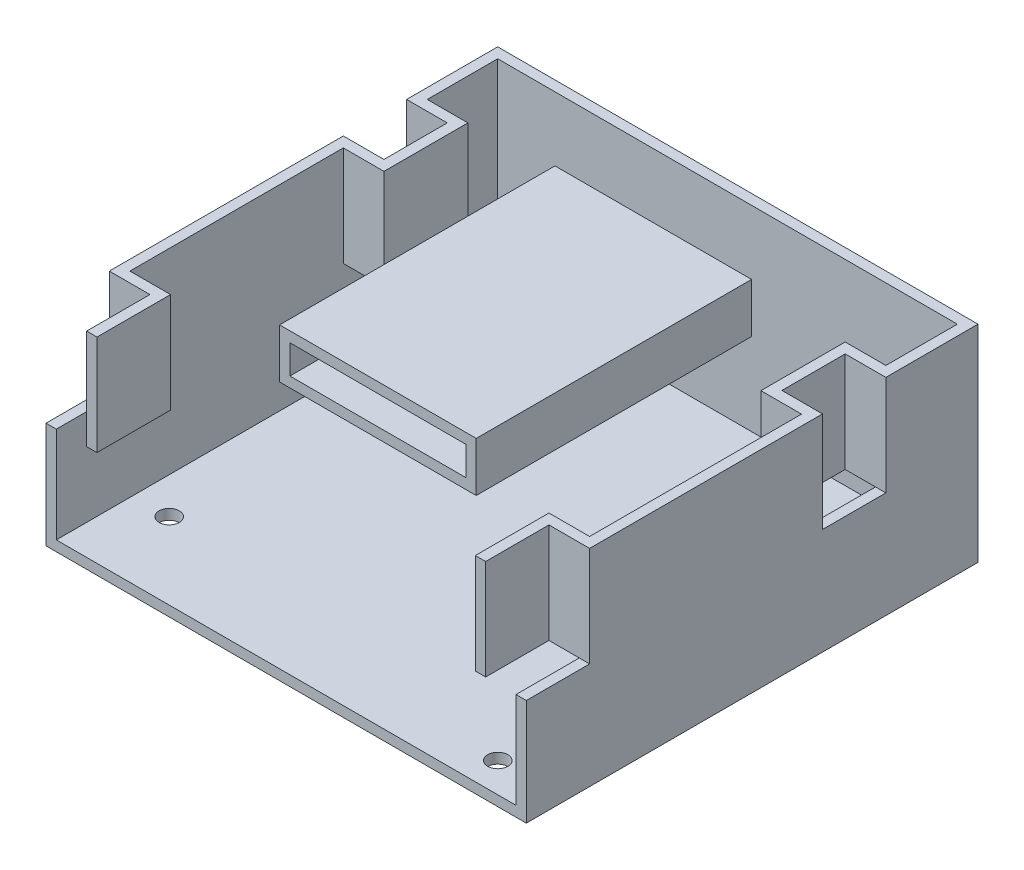
SolidWorks part; units mm, degrees
ref_plane "Front Plane" through (0, 0, 0) normal (0, 0, 1) x (1, 0, 0)
ref_plane "Top Plane" through (0, 0, 0) normal (0, 1, 0) x (1, 0, 0)
ref_plane "Right Plane" through (0, 0, 0) normal (1, 0, 0) x (0, 0, -1)
sketch "Sketch1" plane through (0, 0, 0) normal (0, 1, 0) x (1, 0, 0)
  line L1 (0, 0) -> (89.12, 0)
  line L2 (0, 0) -> (0, 85.57)
  line L3 (0, 85.57) -> (89.12, 85.57)
  line L4 (89.12, 0) -> (89.12, 85.57)
  dimension "D1" = 89.12
  dimension "D2" = 85.57
extrude "Boss-Extrude1" add sketch "Sketch1" along normal blind 2
sketch "Sketch3" plane through (0, 0, 0) normal (0, 0, 1) x (1, 0, 0)
  line L1 (0, 0) -> (-2, 0)
  line L2 (0, 0) -> (0, 30)
  line L3 (0, 30) -> (-2, 30)
  line L4 (-2, 0) -> (-2, 30)
  dimension "D1" = 2
  dimension "D2" = 30
extrude "Boss-Extrude2" add sketch "Sketch3" against normal blind 85.57
sketch "Sketch4" plane through (0, 0, 0) normal (0, 0, 1) x (1, 0, 0)
  line L1 (89.12, 0) -> (91.12, 0)
  line L2 (89.12, 0) -> (89.12, 30)
  line L3 (89.12, 30) -> (91.12, 30)
  line L4 (91.12, 0) -> (91.12, 30)
  dimension "D1" = 30
  dimension "D2" = 2
extrude "Boss-Extrude3" add sketch "Sketch4" against normal blind 85.57
sketch "Sketch5" plane through (0, 0, 0) normal (0, 1, 0) x (1, 0, 0)
  line L1 (-2, 85.57) -> (91.12, 85.57)
  line L2 (-2, 85.57) -> (-2, 87.57)
  line L3 (-2, 87.57) -> (91.12, 87.57)
  line L4 (91.12, 85.57) -> (91.12, 87.57)
  dimension "D1" = 2
extrude "Boss-Extrude4" add sketch "Sketch5" along normal blind 30
sketch "Sketch6" plane through (0, 0, 0) normal (0, 1, 0) x (1, 0, 0)
  line L0 (89.12, 0) -> (89.12, 5.755) construction
  line L1 (89.12, 0) -> (89.12, 85.57) construction
  line L2 (89.12, 5.755) -> (79.835, 5.755) construction
  line L3 (79.835, 5.755) -> (79.835, 0) construction
  line L4 (0, 0) -> (89.12, 0) construction
  circle A0 centre (79.835, 5.755) radius 1.96
  dimension "D3" = 3.92
extrude "Cut-Extrude2" cut sketch "Sketch6" along normal blind 30
sketch "Sketch7" plane through (0, 2, 0) normal (0, 1, 0) x (1, 0, 0)
  line L0 (89.12, 85.57) -> (82.285, 85.57) construction
  line L1 (0, 85.57) -> (89.12, 85.57) construction
  line L2 (82.285, 85.57) -> (82.285, 76.225) construction
  line L3 (82.285, 76.225) -> (89.12, 76.225) construction
  line L4 (89.12, 0) -> (89.12, 85.57) construction
  circle A0 centre (82.285, 76.225) radius 1.96
  dimension "D3" = 3.92
  dimension "D1" = 6.835
extrude "Cut-Extrude3" cut sketch "Sketch7" against normal blind 30
sketch "Sketch8" plane through (0, 0, 0) normal (0, 1, 0) x (1, 0, 0)
  line L0 (0, 85.57) -> (6.985, 85.57) construction
  line L1 (0, 85.57) -> (89.12, 85.57) construction
  line L2 (6.985, 85.57) -> (6.985, 78.28) construction
  line L3 (6.985, 78.28) -> (0, 78.28) construction
  line L4 (0, 85.57) -> (0, 0) construction
  circle A0 centre (6.985, 78.28) radius 1.96
  dimension "D3" = 3.92
  dimension "D1" = 7.29
extrude "Cut-Extrude4" cut sketch "Sketch8" along normal blind 30
sketch "Sketch9" plane through (0, 2, 0) normal (0, 1, 0) x (1, 0, 0)
  line L0 (0, 0) -> (0, 14.85) construction
  line L1 (0, 85.57) -> (0, 0) construction
  line L2 (0, 14.85) -> (7.035, 14.85) construction
  line L3 (7.035, 14.85) -> (7.035, 0) construction
  line L4 (0, 0) -> (89.12, 0) construction
  circle A0 centre (7.035, 14.85) radius 1.96
  dimension "D3" = 3.92
  dimension "D1" = 14.85
extrude "Cut-Extrude5" cut sketch "Sketch9" against normal blind 30
sketch "Sketch10" plane through (89.12, 0, 0) normal (-1, 0, 0) x (0, 0, 1)
  line L0 (0, 2) -> (0, 16.1) construction
  line L1 (0, 30) -> (0, 2) construction
  line L2 (0, 16.1) -> (-32.6241, 16.1) construction
  line L3 (-32.6241, 16.1) -> (-32.6241, 2) construction
  line L4 (0, 2) -> (-85.57, 2) construction
  line L5 (-32.6241, 16.1) -> (-32.6241, 30) construction
  line L6 (-85.57, 30) -> (0, 30) construction
  dimension "D1" = 14.1
sketch "Sketch11" plane through (0, 30, 0) normal (0, 1, 0) x (1, 0, 0)
  line L1 (89.12, 0) -> (83.24, 0)
  line L2 (89.12, 0) -> (89.12, 12.27)
  line L3 (89.12, 12.27) -> (83.24, 12.27)
  line L4 (83.24, 0) -> (83.24, 12.27)
  line L5 (83.24, 0) -> (81.24, 0)
  line L6 (83.24, 0) -> (83.24, 12.27)
  line L7 (83.24, 12.27) -> (81.24, 12.27)
  line L8 (81.24, 0) -> (81.24, 12.27)
  line L9 (81.24, 12.27) -> (89.12, 12.27)
  line L10 (81.24, 12.27) -> (81.24, 14.27)
  line L11 (81.24, 14.27) -> (89.12, 14.27)
  line L12 (89.12, 12.27) -> (89.12, 14.27)
  line M8 (89.12, 85.57) -> (89.12, 0)
  dimension "D1" = 5.88
  dimension "D2" = 12.27
  dimension "D3" = 2
  dimension "D4" = 2
extrude "Boss-Extrude5" add sketch "Sketch11" against normal blind 9.4 contours L11 L10 L7 L3 M8 | L8 L5 L4 L7
sketch "Sketch12" plane through (0, 30, 0) normal (0, 1, 0) x (1, 0, 0)
  line L1 (89.12, 12.27) -> (91.12, 12.27)
  line L2 (89.12, 12.27) -> (89.12, 0)
  line L3 (89.12, 0) -> (91.12, 0)
  line L4 (91.12, 12.27) -> (91.12, 0)
extrude "Cut-Extrude6" cut sketch "Sketch12" against normal blind 9.4
sketch "Sketch13" plane through (0, 30, 0) normal (0, 1, 0) x (1, 0, 0)
  line L0 (89.12, 85.57) -> (89.12, 57.43) construction
  line L1 (89.12, 85.57) -> (89.12, 14.27) construction
  line L3 (89.12, 57.43) -> (83.24, 57.43)
  line L4 (89.12, 57.43) -> (89.12, 69.7)
  line L5 (89.12, 69.7) -> (83.24, 69.7)
  line L6 (83.24, 57.43) -> (83.24, 69.7)
  line L7 (83.24, 69.7) -> (81.24, 69.7)
  line L8 (83.24, 69.7) -> (83.24, 57.43)
  line L9 (83.24, 57.43) -> (81.24, 57.43)
  line L10 (81.24, 69.7) -> (81.24, 57.43)
  line L11 (81.24, 57.43) -> (89.12, 57.43)
  line L12 (81.24, 57.43) -> (81.24, 55.3598)
  line L13 (81.24, 55.3598) -> (89.12, 55.3598)
  line L14 (89.12, 57.43) -> (89.12, 55.3598)
  line L15 (81.24, 69.7) -> (89.12, 69.7)
  line L16 (81.24, 69.7) -> (81.24, 71.7)
  line L17 (81.24, 71.7) -> (89.12, 71.7)
  line L18 (89.12, 69.7) -> (89.12, 71.7)
  line M25 (89.12, 85.57) -> (89.12, 14.27)
  dimension "D1" = 28.14
  dimension "D2" = 12.27
  dimension "D3" = 5.88
  dimension "D4" = 2
  dimension "D5" = 2.0702
  dimension "D6" = 2
extrude "Boss-Extrude6" add sketch "Sketch13" against normal blind 9.4 contours L17 L16 L7 L5 M25 | L7 L10 L9 L6 | L12 L13 L3 L9 M25
sketch "Sketch14" plane through (0, 30, 0) normal (0, 1, 0) x (1, 0, 0)
  line L0 (91.12, 87.57) -> (91.12, 12.27) construction
  line L1 (89.12, 69.7) -> (91.12, 69.7)
  line L2 (89.12, 69.7) -> (89.12, 57.43)
  line L3 (89.12, 57.43) -> (91.12, 57.43)
  line L4 (91.12, 69.7) -> (91.12, 57.43)
extrude "Cut-Extrude7" cut sketch "Sketch14" against normal blind 9.4
sketch "Sketch15" plane through (0, 30, 0) normal (0, 1, 0) x (1, 0, 0)
  line L0 (0, 85.57) -> (0, 57.64) construction
  line L1 (0, 85.57) -> (0, 0) construction
  line L3 (0, 57.64) -> (5.88, 57.64)
  line L4 (0, 57.64) -> (0, 69.91)
  line L5 (0, 69.91) -> (5.88, 69.91)
  line L6 (5.88, 57.64) -> (5.88, 69.91)
  line L7 (5.88, 69.91) -> (7.88, 69.91)
  line L8 (5.88, 69.91) -> (5.88, 57.64)
  line L9 (5.88, 57.64) -> (7.88, 57.64)
  line L10 (7.88, 69.91) -> (7.88, 57.64)
  line L11 (0, 57.64) -> (7.88, 57.64)
  line L12 (0, 57.64) -> (0, 55.64)
  line L13 (0, 55.64) -> (7.88, 55.64)
  line L14 (7.88, 57.64) -> (7.88, 55.64)
  line L15 (0, 69.91) -> (7.88, 69.91)
  line L16 (0, 69.91) -> (0, 71.91)
  line L17 (0, 71.91) -> (7.88, 71.91)
  line L18 (7.88, 69.91) -> (7.88, 71.91)
  line M12 (0, 0) -> (0, 85.57)
  dimension "D1" = 27.93
  dimension "D2" = 5.88
  dimension "D3" = 12.27
  dimension "D4" = 2
  dimension "D5" = 2
  dimension "D6" = 2
extrude "Boss-Extrude7" add sketch "Sketch15" against normal blind 9.4 contours L7 L18 L17 L5 M12 | L10 L7 L6 L9 | L14 L9 L3 L13 M12
sketch "Sketch16" plane through (0, 30, 0) normal (0, 1, 0) x (1, 0, 0)
  line L0 (-2, 87.57) -> (-2, 0) construction
  line L1 (-2, 69.91) -> (0, 69.91)
  line L2 (-2, 69.91) -> (-2, 57.64)
  line L3 (-2, 57.64) -> (0, 57.64)
  line L4 (0, 69.91) -> (0, 57.64)
extrude "Cut-Extrude8" cut sketch "Sketch16" against normal blind 9.4
sketch "Sketch17" plane through (0, 30, 0) normal (0, 1, 0) x (1, 0, 0)
  line L0 (0, 0) -> (89.12, 0) construction
  line L1 (0, 0) -> (5.88, 0)
  line L2 (0, 0) -> (0, 12.27)
  line L3 (0, 12.27) -> (5.88, 12.27)
  line L4 (5.88, 0) -> (5.88, 12.27)
  line L5 (5.88, 12.27) -> (7.88, 12.27)
  line L6 (5.88, 12.27) -> (5.88, 0)
  line L7 (5.88, 0) -> (7.88, 0)
  line L8 (7.88, 12.27) -> (7.88, 0)
  line L9 (0, 55.64) -> (0, 0) construction
  line L10 (7.88, 12.27) -> (0, 12.27)
  line L11 (7.88, 12.27) -> (7.88, 14.27)
  line L12 (7.88, 14.27) -> (0, 14.27)
  line L13 (0, 12.27) -> (0, 14.27)
  line M13 (0, 0) -> (0, 55.64)
  dimension "D1" = 12.27
  dimension "D2" = 5.88
  dimension "D3" = 2
  dimension "D4" = 2
extrude "Boss-Extrude8" add sketch "Sketch17" against normal blind 9.4 contours L11 L12 L3 L5 M13 | L8 L5 L4 L7
sketch "Sketch18" plane through (0, 30, 0) normal (0, 1, 0) x (1, 0, 0)
  line L0 (-2, 57.64) -> (-2, 0) construction
  line L1 (0, 0) -> (-2, 0)
  line L2 (0, 0) -> (0, 12.27)
  line L3 (0, 12.27) -> (-2, 12.27)
  line L4 (-2, 0) -> (-2, 12.27)
extrude "Cut-Extrude9" cut sketch "Sketch18" against normal blind 9.4
sketch "Sketch19" plane through (0, 30, 0) normal (0, 1, 0) x (1, 0, 0)
  line L0 (83.24, 0) -> (81.24, 0)
  line L1 (81.24, 0) -> (81.24, 14.27)
  line L2 (81.24, 0) -> (81.24, 14.27) construction
  line L3 (81.24, 14.27) -> (89.12, 14.27)
  line L4 (89.12, 14.27) -> (89.12, 55.3598)
  line L5 (89.12, 55.3598) -> (81.24, 55.3598)
  line L6 (81.24, 55.3598) -> (81.24, 71.7)
  line L7 (81.24, 71.7) -> (89.12, 71.7)
  line L8 (89.12, 71.7) -> (89.12, 85.57)
  line L9 (89.12, 85.57) -> (0, 85.57)
  line L10 (0, 85.57) -> (0, 71.91)
  line L11 (0, 71.91) -> (7.88, 71.91)
  line L12 (7.88, 71.91) -> (7.88, 55.64)
  line L13 (7.88, 55.64) -> (0, 55.64)
  line L14 (0, 55.64) -> (0, 14.27)
  line L15 (0, 14.27) -> (7.88, 14.27)
  line L16 (7.88, 14.27) -> (7.88, 0)
  line L17 (7.88, 0) -> (5.88, 0)
  line L18 (5.88, 0) -> (5.88, 12.27)
  line L19 (5.88, 12.27) -> (-2, 12.27)
  line L20 (-2, 12.27) -> (-2, 57.64)
  line L21 (-2, 57.64) -> (5.88, 57.64)
  line L22 (5.88, 57.64) -> (5.88, 69.91)
  line L23 (5.88, 69.91) -> (-2, 69.91)
  line L24 (-2, 69.91) -> (-2, 87.57)
  line L25 (-2, 87.57) -> (91.12, 87.57)
  line L26 (91.12, 87.57) -> (91.12, 69.7)
  line L27 (91.12, 69.7) -> (83.24, 69.7)
  line L28 (83.24, 69.7) -> (83.24, 57.43)
  line L29 (83.24, 57.43) -> (91.12, 57.43)
  line L30 (91.12, 57.43) -> (91.12, 12.27)
  line L31 (91.12, 12.27) -> (83.24, 12.27)
  line L32 (83.24, 12.27) -> (83.24, 0)
extrude "Boss-Extrude9" add sketch "Sketch19" along normal blind 10
sketch "Sketch20" plane through (0, 2, 0) normal (0, 1, 0) x (1, 0, 0)
  line L0 (0, 85.57) -> (27.1, 85.57) construction
  line L1 (89.12, 85.57) -> (0, 85.57) construction
  line L2 (27.1, 85.57) -> (27.1, 43.02) construction
  line L3 (27.1, 43.02) -> (11.1, 43.02) construction
  line L4 (11.1, 43.02) -> (11.1, 85.57) construction
  line L6 (11.1, 85.57) -> (27.1, 85.57)
  line L7 (11.1, 85.57) -> (11.1, 43.02)
  line L8 (11.1, 43.02) -> (27.1, 43.02)
  line L9 (27.1, 85.57) -> (27.1, 43.02)
  dimension "D1" = 42.55
  dimension "D2" = 27.1
  dimension "D3" = 16
extrude "Boss-Extrude10" add sketch "Sketch20" along normal blind 8.88
sketch "Sketch21" plane through (0, 0, -43.02) normal (0, 0, 1) x (1, 0, 0)
  line L0 (27.1, 10.88) -> (27.1, 2) construction
  line L1 (11.1, 10.88) -> (27.1, 10.88)
  line L2 (11.1, 10.88) -> (11.1, 8.88)
  line L3 (11.1, 8.88) -> (27.1, 8.88)
  line L4 (27.1, 10.88) -> (27.1, 8.88)
  line L6 (11.1, 8.88) -> (27.1, 8.88)
  line L7 (11.1, 8.88) -> (11.1, 2)
  line L8 (11.1, 2) -> (27.1, 2)
  line L9 (27.1, 8.88) -> (27.1, 2)
  line M2 (11.1, 2) -> (27.1, 2)
  line M3 (27.1, 2) -> (27.1, 10.88)
  line M5 (11.1, 10.88) -> (11.1, 2)
  dimension "D1" = 2
extrude "Cut-Extrude10" cut sketch "Sketch21" against normal blind 42.55 contours L3 M5 M2 M3
sketch "Sketch22" plane through (0, 0, -85.57) normal (0, 0, 1) x (1, 0, 0)
  line L0 (11.1, 10.88) -> (11.1, 17.9689) construction
  line L2 (11.1, 17.9689) -> (49.22, 17.9689)
  line L3 (11.1, 17.9689) -> (11.1, 27.5589)
  line L4 (11.1, 27.5589) -> (49.22, 27.5589)
  line L5 (49.22, 17.9689) -> (49.22, 27.5589)
  dimension "D1" = 38.12
  dimension "D2" = 9.59
extrude "Boss-Extrude11" add sketch "Sketch22" along normal blind 53.38
sketch "Sketch23" plane through (0, 0, -32.19) normal (0, 0, 1) x (1, 0, 0)
  line L0 (13.1, 27.5589) -> (13.1, 25.5589) construction
  line L1 (49.22, 27.5589) -> (11.1, 27.5589) construction
  line L2 (13.1, 25.5589) -> (11.1, 25.5589) construction
  line L3 (11.1, 27.5589) -> (11.1, 17.9689) construction
  line L4 (47.22, 17.9689) -> (47.22, 19.9689) construction
  line L5 (11.1, 17.9689) -> (49.22, 17.9689) construction
  line L6 (47.22, 19.9689) -> (49.22, 19.9689) construction
  line L7 (49.22, 17.9689) -> (49.22, 27.5589) construction
  line L9 (13.1, 25.5589) -> (47.22, 25.5589)
  line L10 (13.1, 25.5589) -> (13.1, 19.9689)
  line L11 (13.1, 19.9689) -> (47.22, 19.9689)
  line L12 (47.22, 25.5589) -> (47.22, 19.9689)
  dimension "D1" = 2
  dimension "D2" = 2
  dimension "D3" = 2
  dimension "D4" = 2
extrude "Cut-Extrude11" cut sketch "Sketch23" against normal blind 53.38
equation "\"tol1\"= 0.1cm"
equation "\"D1@Sketch1\"=8.812cm +\"tol1\""
equation "\"D2@Sketch1\"=8.457cm +\"tol1\""
equation "\"D1@Boss-Extrude2\"=8.457 +\"tol1\""
equation "\"D1@Boss-Extrude3\"=8.457 +\"tol1\""
equation "\"D1@Sketch6\"=0.5255 + \"tol2\""
equation "\"hole\"= 0.392cm"
equation "\"D3@Sketch6\"=\"hole\""
equation "\"tol2\"= \"tol1\" / 2"
equation "\"D2@Sketch6\"=0.8785 + \"tol2\""
equation "\"D2@Sketch9\"=0.6535 + \"tol2\""
equation "\"D3@Sketch9\"=\"hole\""
equation "\"D1@Sketch9\"=1.435 + \"tol2\""
equation "\"D2@Sketch8\"=0.6485 + \"tol2\""
equation "\"D1@Sketch8\"=0.679 + \"tol2\""
equation "\"D3@Sketch8\"=\"hole\""
equation "\"D3@Sketch7\"=\"hole\""
equation "\"D2@Sketch7\"=0.8845 + \"tol2\""
equation "\"D1@Sketch7\"=0.6335 + \"tol2\""
equation "\"heightTol\"= 0.05cm"
equation "\"D1@Sketch10\"=1.36 + \"heightTol\""
equation "\"D2@Sketch20\"=2.61 + \"tol1\""
equation "\"D1@Boss-Extrude10\"=0.588 + \"tol1\" +0.2"
equation "\"batTol\"= 0.05cm"
equation "\"D1@Sketch22\"=3.362+0.4 +\"batTol\""
equation "\"D2@Sketch22\"=0.509+0.4 + \"batTol\""
equation "\"D1@Boss-Extrude11\"=5.288 + \"batTol\""
equation "\"D1@Cut-Extrude11\"=5.288 + \"batTol\""
